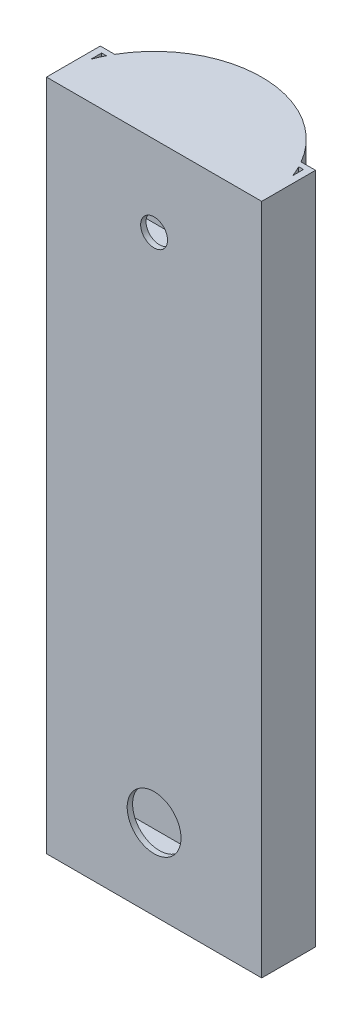
SolidWorks part; units mm, degrees
ref_plane "Front Plane" through (0, 0, 0) normal (0, 0, 1) x (1, 0, 0)
ref_plane "Top Plane" through (0, 0, 0) normal (0, 1, 0) x (1, 0, 0)
ref_plane "Right Plane" through (0, 0, 0) normal (1, 0, 0) x (0, 0, -1)
sketch "Sketch1" plane through (0, 0, 0) normal (0, 1, 0) x (1, 0, 0)
  line L1 (40, -10) -> (-40, -10)
  line L2 (40, -10) -> (40, 10)
  line L3 (40, 10) -> (-40, 10)
  line L4 (-40, -10) -> (-40, 10)
  line L5 (40, -10) -> (-40, 10) construction
  line L6 (40, 10) -> (-40, -10) construction
  point P0 (0, 0)
  dimension "D1" = 80
  dimension "D2" = 20
extrude "Boss-Extrude1" add sketch "Sketch1" along normal blind 200
sketch "Sketch2" plane through (0, 200, 0) normal (0, 1, 0) x (1, 0, 0)
  line L1 (37.5, -8) -> (-37.5, -8)
  line L2 (37.5, -8) -> (37.5, 8)
  line L3 (37.5, 8) -> (-37.5, 8)
  line L4 (-37.5, -8) -> (-37.5, 8)
  line L5 (37.5, -8) -> (-37.5, 8) construction
  line L6 (37.5, 8) -> (-37.5, -8) construction
  point P0 (0, 0)
  dimension "D1" = 75
  dimension "D2" = 16
extrude "Cut-Extrude1" cut sketch "Sketch2" against normal blind 190 from surface at 0 contours L4 L1 L2 L3 starting at face at (0, 200, 0)
sketch "Sketch3" plane through (0, 0, -10) normal (0, 0, -1) x (-1, 0, 0)
  line L0 (-40, 200) -> (40, 200) construction
  line L1 (-40, 200) -> (-40, 0) construction
  circle A0 centre (0, 40) radius 7.5
  dimension "D3" = 15
  dimension "D1" = 160
  dimension "D2" = 40
extrude "Cut-Extrude3" cut sketch "Sketch3" against normal blind 10 from surface at 0 contours A0 starting at face at (0, 100, -10)
sketch "Sketch4" plane through (0, 200, 0) normal (0, 1, 0) x (1, 0, 0)
  line L0 (-40, 10) -> (-40, -10)
  line L1 (-40, 10) -> (-40, -10) construction
  line L2 (-40, -10) -> (40, -10)
  line L3 (40, -10) -> (40, 10)
  line L4 (40, 10) -> (-40, 10)
  line L5 (-37.5, 8) -> (-37.5, -8)
  line L6 (-37.5, -8) -> (37.5, -8)
  line L7 (37.5, -8) -> (37.5, 8)
  line L8 (37.5, 8) -> (-37.5, 8)
  line M5 (-40, 10) -> (-40, -10)
  line M6 (-40, -10) -> (40, -10)
  line M7 (40, -10) -> (40, 10)
  line M8 (40, 10) -> (-40, 10)
  line M9 (-37.5, 8) -> (37.5, 8)
  line M10 (37.5, 8) -> (37.5, -8)
  line M11 (37.5, -8) -> (-37.5, -8)
  line M12 (-37.5, -8) -> (-37.5, 8)
extrude "Boss-Extrude2" add sketch "Sketch4" along normal blind 50 contours M8 M5 M6 M7 M12 M9 M10 M11
sketch "Sketch5" plane through (0, 0, 10) normal (0, 0, 1) x (1, 0, 0)
  line L0 (-40, 250) -> (40, 250) construction
  line L3 (40, 250) -> (40, 0) construction
  circle A0 centre (0, 220) radius 5
  dimension "D1" = 10
  dimension "D2" = 30
  dimension "D3" = 40
extrude "Cut-Extrude4" cut sketch "Sketch5" against normal blind 10 contours A0
sketch "Sketch6" plane through (0, 0, 10) normal (0, 0, 1) x (1, 0, 0)
  line L0 (0, 0) -> (0, 263.9582) construction
  line L1 (0, 250) -> (40, 250)
  line L2 (-40, 250) -> (40, 250) construction
  line L3 (40, 250) -> (40, 200)
  line L4 (40, 250) -> (40, 0) construction
  line L5 (40, 200) -> (0, 200)
  line L6 (0, 200) -> (0, 205)
  line L7 (0, 205) -> (35, 205)
  line L8 (35, 205) -> (35, 245)
  line L9 (35, 245) -> (0, 245)
  line L10 (0, 245) -> (0, 250)
  dimension "D1" = 5
  dimension "D2" = 40
  dimension "D3" = 5
  dimension "D4" = 5
revolve "Revolve1" add sketch "Sketch6" angle 180 about L0
sketch "Sketch7" plane through (0, 200, 0) normal (0, -1, 0) x (1, 0, 0)
  line L0 (34.641, -10) -> (-34.641, -10) construction
  circle A0 centre (0, -20) radius 5
  dimension "D1" = 10
  dimension "D2" = 10
sketch "Sketch8" plane through (0, 0, 10) normal (0, 0, 1) x (1, 0, 0)
  line L0 (-40, 250) -> (-40, 0) construction
  line L1 (-40, 0) -> (40, 0) construction
  circle A0 centre (0, 30) radius 10
  point P4 (0, 0)
  dimension "D2" = 20
  dimension "D1" = 40
  dimension "D3" = 30
extrude "Cut-Extrude5" cut sketch "Sketch8" against normal blind 10 contours A0
extrude "Boss-Extrude3" add sketch "Sketch7" along normal blind 15
sketch "Sketch9" plane through (0, 185, 0) normal (0, -1, 0) x (1, 0, 0)
  circle A0 centre (0, -20) radius 4
  dimension "D1" = 8
extrude "Cut-Extrude6" cut sketch "Sketch9" against normal blind 30 contours A0
